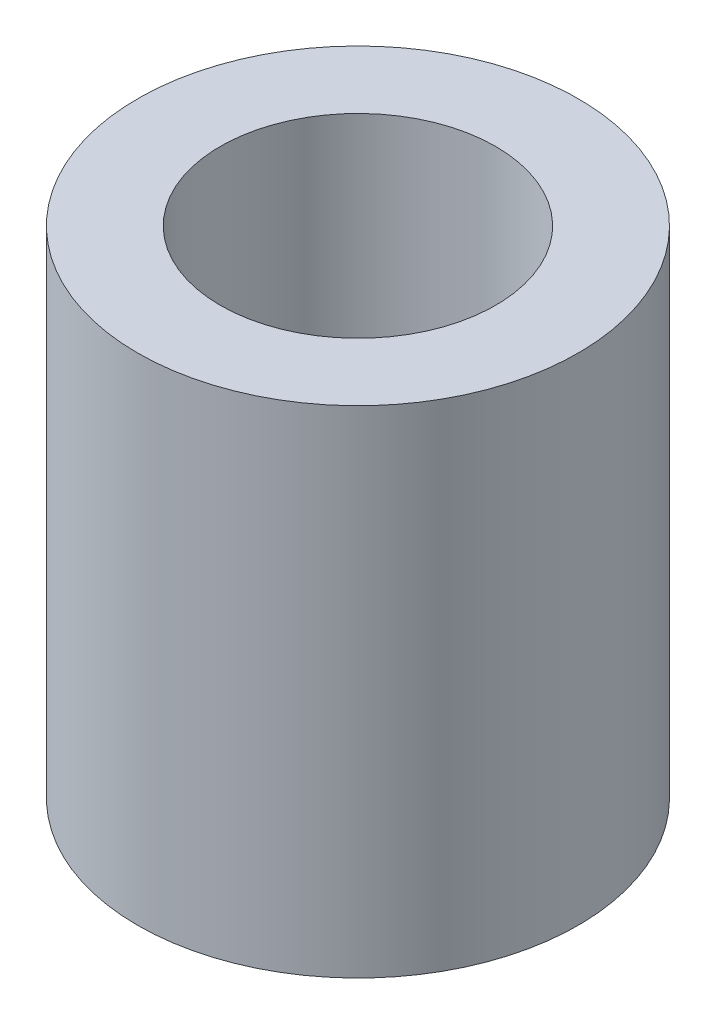
SolidWorks part; units mm, degrees
ref_plane "Front Plane" through (0, 0, 0) normal (0, 0, 1) x (1, 0, 0)
ref_plane "Top Plane" through (0, 0, 0) normal (0, 1, 0) x (1, 0, 0)
ref_plane "Right Plane" through (0, 0, 0) normal (1, 0, 0) x (0, 0, -1)
sketch "Sketch1" plane through (0, 0, 0) normal (0, 1, 0) x (1, 0, 0)
  circle A0 centre (0, 0) radius 10.16
  circle A1 centre (0, 0) radius 6.35
extrude "Boss-Extrude1" add sketch "Sketch1" along normal blind 22.86
